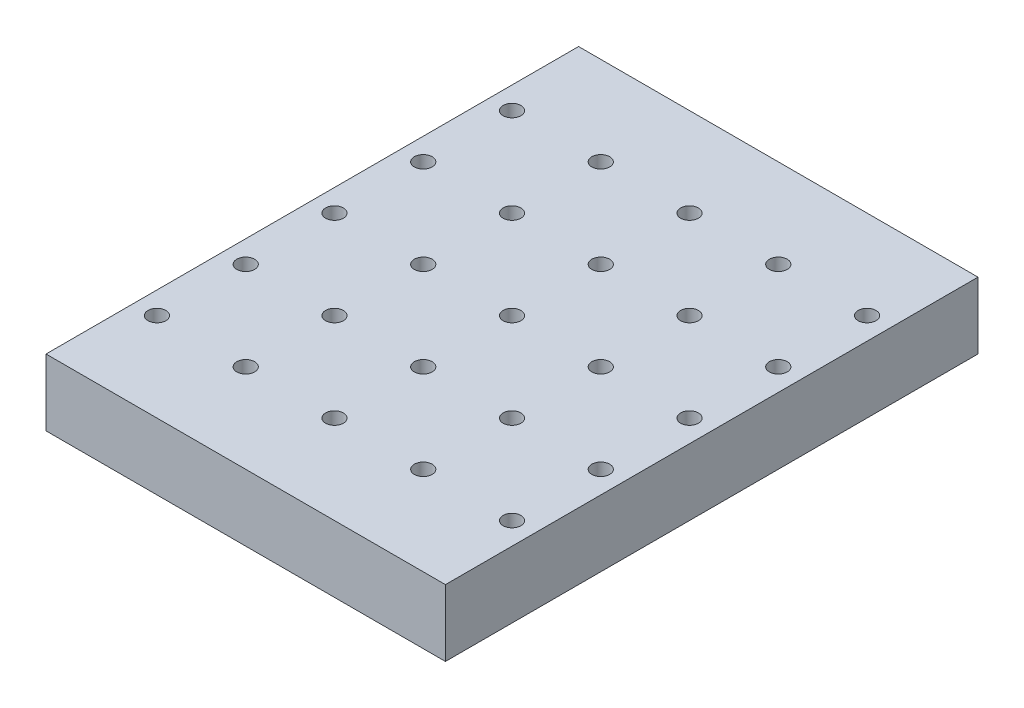
SolidWorks part; units mm, degrees
material "Cast Alloy Steel"
ref_plane "Front Plane" through (0, 0, 0) normal (0, 0, 1) x (1, 0, 0)
ref_plane "Top Plane" through (0, 0, 0) normal (0, 1, 0) x (1, 0, 0)
ref_plane "Right Plane" through (0, 0, 0) normal (1, 0, 0) x (0, 0, -1)
sketch "Sketch1" plane through (0, 0, 0) normal (0, 1, 0) x (1, 0, 0)
  line L1 (57.15, -76.2) -> (-57.15, -76.2)
  line L2 (57.15, -76.2) -> (57.15, 76.2)
  line L3 (57.15, 76.2) -> (-57.15, 76.2)
  line L4 (-57.15, -76.2) -> (-57.15, 76.2)
  line L5 (57.15, -76.2) -> (-57.15, 76.2) construction
  line L6 (57.15, 76.2) -> (-57.15, -76.2) construction
  point P0 (0, 0)
  dimension "D1" = 114.3
  dimension "D2" = 152.4
extrude "Boss-Extrude1" add sketch "Sketch1" along normal blind 19.05
hole_wizard "1/4-20 Tapped Hole1" positions "Sketch2" profile "Sketch3" tap size "1/4-20" standard "ANSI Inch" end condition through all
sketch "Sketch2" plane through (0, 19.05, 0) normal (0, 1, 0) x (1, 0, 0)
  point P4 (0, 0)
sketch "Sketch3" plane through (0, 19.05, 0) normal (1, 0, 0) x (0, 0, 1)
  line L0 (0, 0) -> (0, 19.05)
  line L1 (0, 19.05) -> (2.5527, 19.05)
  line L2 (2.5527, 19.05) -> (2.5527, 0)
  line L5 (2.5527, 0) -> (0, 0)
  line L11 (0, -6.35) -> (0, 107.95) construction
  dimension "Thru Tap Drill Dia." = 5.1054
  dimension "Thru Tap Drill Depth" = 19.05
cosmetic thread "Hole Thread1" parameters "D2"=6.35
pattern_linear "LPattern1" count 3 spacing 25.4 along (0, 0, 1) count 3 spacing 25.4 along (0, 0, -1) of "1/4-20 Tapped Hole1"
pattern_linear "LPattern2" count 3 spacing 25.4 along (1, 0, 0) count 3 spacing 25.4 along (-1, 0, 0) of "LPattern1", "1/4-20 Tapped Hole1"
